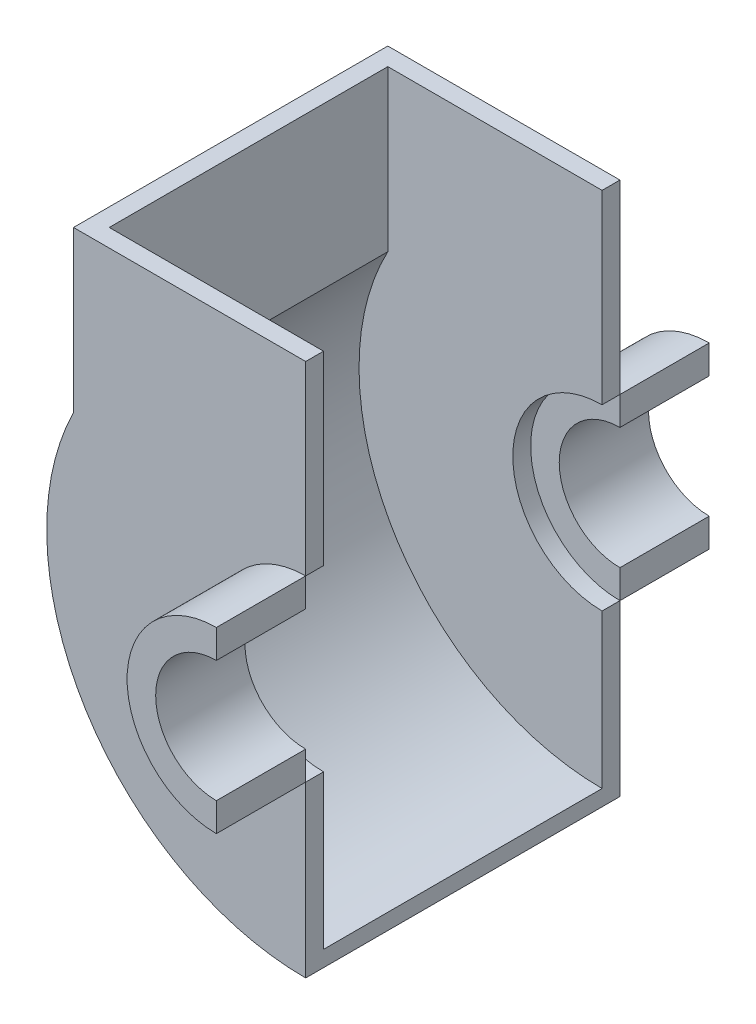
SolidWorks part; units mm, degrees
ref_plane "Front Plane" through (0, 0, 0) normal (0, 0, 1) x (1, 0, 0)
ref_plane "Top Plane" through (0, 0, 0) normal (0, 1, 0) x (1, 0, 0)
ref_plane "Right Plane" through (0, 0, 0) normal (1, 0, 0) x (0, 0, -1)
sketch "Sketch1" plane through (0, 0, 0) normal (0, 0, 1) x (1, 0, 0)
  line L0 (0, 25) -> (0, 17)
  line L1 (0, -17) -> (0, -25)
  arc A0 (0, 17) -> (0, -17) centre (0, 0) ccw
  arc A1 (0, 25) -> (0, -25) centre (0, 0) ccw
  dimension "D1" = 50
  dimension "D2" = 34
extrude "Boss-Extrude1" add sketch "Sketch1" along normal blind 20 and the other way blind 5 contours L0 A0 L1 A1
sketch "Sketch2" plane through (0, 0, 20) normal (0, 0, 1) x (1, 0, 0)
  line L0 (0, -73.6908) -> (0, -25)
  line L1 (0, -25) -> (0, -34.8216)
  line L2 (0, 25) -> (0, 77)
  line L3 (0, 77) -> (-65, 77)
  line L4 (-65, 77) -> (-65, 32.1131)
  circle A0 centre (0, 0) radius 3.4593
  circle A1 centre (0, -3.4593) radius 0.5863
  arc A2 (-65, 32.1131) -> (0, -72.5) centre (0, 0) ccw
  arc M1 (0, 25) -> (0, -25) centre (0, 0) ccw
  dimension "D1" = 145
  dimension "D2" = 52
  dimension "D3" = 65
extrude "Boss-Extrude2" add sketch "Sketch2" along normal blind 5 separate body contours L4 A2 L0 L2 L3 M1
ref_plane "Plane1" through (0, 0, 64) normal (0, 0, -1) x (-1, 0, 0)
mirror "Mirror5" about plane through (0, 0, 64) normal (0, 0, -1) of bodies 102 101
sketch "Sketch6" plane through (0, 0, 103) normal (0, 0, -1) x (-1, 0, 0)
  line L0 (65, 32.1131) -> (65, 77)
  line L1 (65, 77) -> (60, 77)
  line L2 (0, 77) -> (65, 77) construction
  line L3 (60, 77) -> (60, 32.1131)
  line L5 (0, -68.0533) -> (0, -72.5)
  arc A0 (0, -68.0533) -> (60, 32.1131) centre (0, 0) ccw
  arc A1 (0, -72.5) -> (65, 32.1131) centre (0, 0) ccw
  dimension "D1" = 5
extrude "Boss-Extrude3" add sketch "Sketch6" against normal up to surface (83 mm away) contours L5 A1 L0 L1 L3 A0
equation "\"40mmm\"=10"
